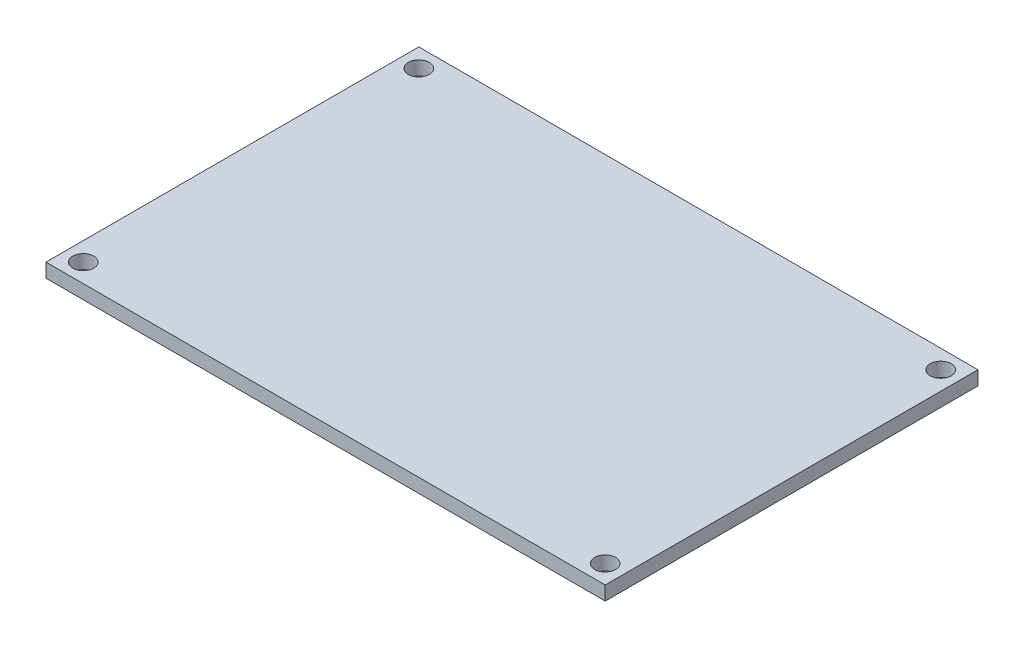
SolidWorks part; units mm, degrees
ref_plane "Front Plane" through (0, 0, 0) normal (0, 0, 1) x (1, 0, 0)
ref_plane "Top Plane" through (0, 0, 0) normal (0, 1, 0) x (1, 0, 0)
ref_plane "Right Plane" through (0, 0, 0) normal (1, 0, 0) x (0, 0, -1)
sketch "Sketch1" plane through (0, 0, 0) normal (0, 1, 0) x (1, 0, 0)
  line L1 (-30, 20) -> (30, 20)
  line L2 (-30, 20) -> (-30, -20)
  line L3 (-30, -20) -> (30, -20)
  line L4 (30, 20) -> (30, -20)
  line L5 (-30, 20) -> (30, -20) construction
  line L6 (-30, -20) -> (30, 20) construction
  circle A0 centre (-28, 18) radius 1.125
  circle A2 centre (28, 18) radius 1.125
  circle A3 centre (28, -18) radius 1.125
  circle A4 centre (-28, -18) radius 1.125
  point P0 (0, 0)
  dimension "D5" = 2.25
  dimension "D1" = 40
  dimension "D2" = 60
  dimension "D3" = 2
  dimension "D4" = 2
  dimension "D6" = 2
  dimension "D7" = 2
extrude "Boss-Extrude1" add sketch "Sketch1" along normal blind 1.5
